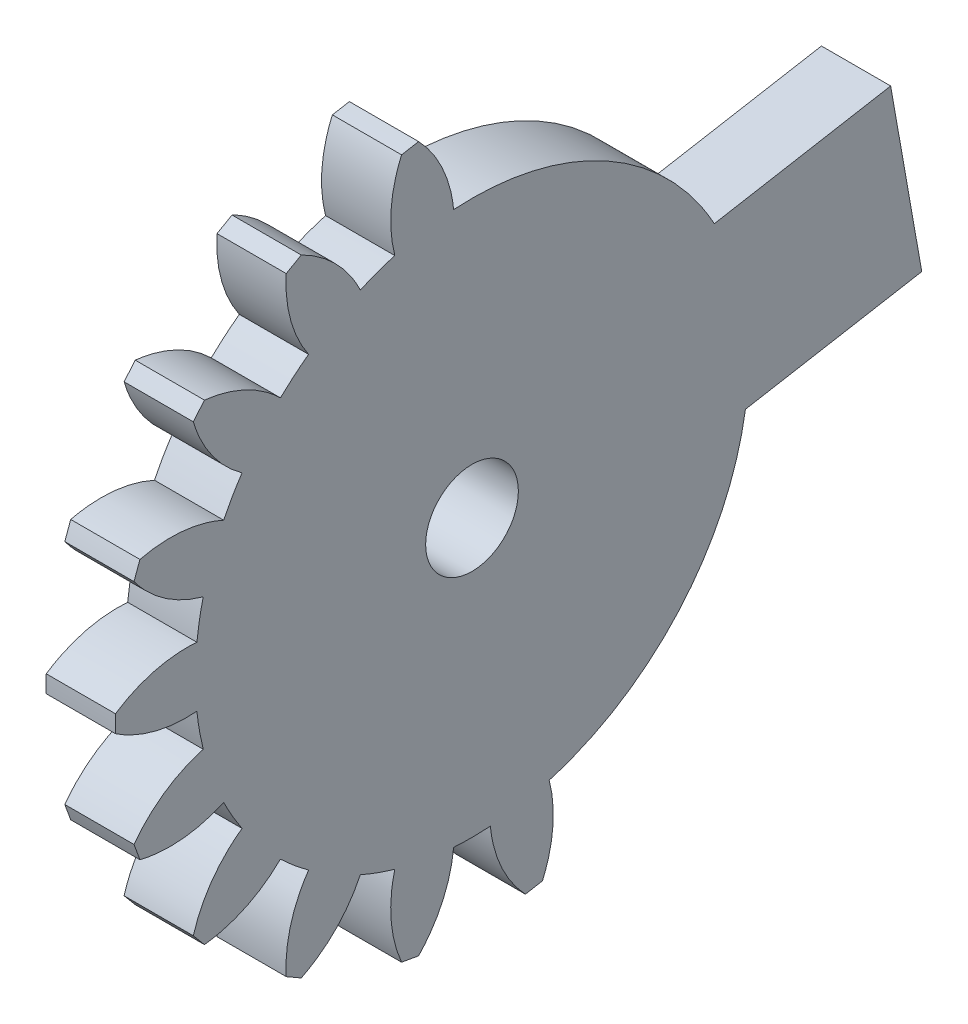
SolidWorks part; units mm, degrees
ref_plane "Plane1" through (0, 0, 0) normal (0, 0, 1) x (1, 0, 0)
ref_plane "Plane2" through (0, 0, 0) normal (0, 1, 0) x (1, 0, 0)
ref_plane "Plane3" through (0, 0, 0) normal (1, 0, 0) x (0, 0, -1)
sketch "HoldingSke" plane through (0, 0, 0) normal (0, 1, 0) x (1, 0, 0)
  line L0 (0, 0) -> (483.1367, -156.9806)
  line L1 (-15, 0) -> (100, 0) construction
  line L2 (0, 0) -> (-2.1039, 2.3779)
  line L3 (0, 0) -> (-11.863, 4.5341)
  line L4 (0, 0) -> (8.2133, 2.6687)
  line L5 (0, 0) -> (-47.5972, -17.7524)
  line L6 (0, 0) -> (-2.632, -1.7758)
  line L7 (-2.1039, 2.3779) -> (8.8308, 51.9871)
  line L8 (-76.2, 54.61) -> (-72.771, 54.61)
  line L9 (-71.009, 38.7566) -> (-53.1078, 45.2721)
  line L10 (-76.2, 71.12) -> (104.1128, 71.12)
  line L11 (0, 0) -> (-3.175, 0)
  line L12 (-76.2, 101.6) -> (-76.1492, 101.6)
  line L13 (24.9733, 27.94) -> (52.9518, 28.4284)
  line L14 (24.9733, 27.94) -> (25.0241, 27.9398)
  line L15 (24.9733, 27.94) -> (100.4021, 29.52)
  circle A0 centre (0, 0) radius 1.5875
  circle A1 centre (0, 0) radius 9.8552
  circle A2 centre (0, 0) radius 38.1
  circle A3 centre (0, 0) radius 1.5875
  dimension "MHD" = 19.7104
  dimension "Hub_dia" = 76.2
  dimension "Bore" = 3.175
  dimension "MBD" = 3.175
  dimension "Num_teeth" = 18
  dimension "Pitch_radius" = 180.3128
  dimension "Pitch" = 508
  dimension "Width" = 3.175
  dimension "Overall_len" = 50.8
  dimension "Show_teeth" = 18
  dimension "Thickness" = 3.175
  dimension "OAL" = 50.8001
  dimension "T_dim" = 3.429
  dimension "Ap" = 20
  dimension "H" = 19.05
  dimension "Backlash" = 0.0508
  dimension "Addendum_fac" = 1
  dimension "Dedendum_fac" = 1.2
  dimension "Clearance_fac" = 0.2
  dimension "Dedendum_add" = 0.0508
sketch "BasProSke" plane through (0, 0, 0) normal (0, 1, 0) x (1, 0, 0)
  line L0 (-10, 0) -> (60, 0) construction
  line L1 (0, 0) -> (0, 12.7)
  line L2 (0, 0) -> (3.175, 0)
  line L3 (3.175, 0) -> (3.175, 12.7)
  line L4 (3.175, 12.7) -> (0, 12.7)
  dimension "Diameter" = 25.4
  dimension "Thickness" = 3.175
revolve "Base-Revolve" add sketch "BasProSke" angle 360 about L0
sketch "TooCutSke" plane through (0, 0, 0) normal (1, 0, 0) x (0, 0, -1)
  line L1 (0, 0) -> (0, 107) construction
  line L2 (0, 0) -> (-1.085, 11.3784) construction
  line L3 (0, 0) -> (-3.9571, 22.4417) construction
  line L4 (-1.085, 11.3784) -> (-1.9785, 11.2208) construction
  arc A0 (0.6537, 9.8335) -> (-0.6537, 9.8335) centre (0, 0) ccw
  arc A1 (1.9234, 12.5792) -> (-1.9234, 12.5792) centre (0, 0) ccw
  circle A2 centre (0, 0) radius 11.43 construction
  circle A3 centre (0, 0) radius 10.7407 construction
  arc A4 (-0.6537, 9.8335) -> (-1.9234, 12.5792) centre (-5.2046, 9.3954) ccw
  arc A5 (1.9234, 12.5792) -> (0.6537, 9.8335) centre (5.2046, 9.3954) ccw
  dimension "Root_dia" = 19.7104
  dimension "Overcut_dia" = 25.4508
  dimension "Pitch_dia" = 22.86
  dimension "Base_dia" = 21.4814
  dimension "Flank_rad" = 4.572
  dimension "Half_ang" = 10
  dimension "Half_CT" = 0.9073
extrude "ToothCut" cut sketch "TooCutSke" along normal through all
fillet "Breaks" [suppressed] radius 0.0254
fillet "RootFillets" [suppressed] radius 0.3048
pattern_circular "TeethCuts" count 18 every 20 about axis through (-10, 0, 0) along (1, 0, 0) of "ToothCut", "RootFillets", "Breaks"
sketch "HubNeaOneSke" plane through (0, 0, 0) normal (-1, 0, 0) x (0, 0, 1)
  circle A0 centre (0, 0) radius 9.8552
  dimension "Diameter" = 19.7104
extrude "HubNearOne" [suppressed] add sketch "HubNeaOneSke" along normal blind 47.6251
sketch "HubNeaBotSke" plane through (0, 0, 0) normal (-1, 0, 0) x (0, 0, 1)
  circle A0 centre (0, 0) radius 9.8552
  dimension "Diameter" = 19.7104
extrude "HubNearBoth" [suppressed] add sketch "HubNeaBotSke" along normal blind 23.8125
ref_plane "FarPln" through (3.175, 0, 0) normal (1, 0, 0) x (0, 0, -1)
sketch "HubFarSke" plane through (3.175, 0, 0) normal (1, 0, 0) x (0, 0, -1)
  circle A0 centre (0, 0) radius 9.8552
  dimension "Diameter" = 19.7104
extrude "HubFar" [suppressed] add sketch "HubFarSke" along normal blind 23.8125
sketch "BorSke" plane through (0, 0, 0) normal (1, 0, 0) x (0, 0, -1)
  circle A0 centre (0, 0) radius 1.5875
  dimension "Diameter" = 3.175
extrude "Bore" cut sketch "BorSke" along normal mid plane 101.6001
sketch "KeySke" plane through (0, 0, 0) normal (1, 0, 0) x (0, 0, -1)
  line L0 (-0.127, 0) -> (-0.127, 1.8415)
  line L1 (-0.127, 1.8415) -> (0.127, 1.8415)
  line L2 (0.127, 1.8415) -> (0.127, 0)
  line L3 (0, 0) -> (0, 34) construction
  line L4 (-0.127, 0) -> (0.127, 0)
  dimension "Offset" = 1.8415
  dimension "Width" = 0.254
extrude "Keyway" [suppressed] cut sketch "KeySke" along normal mid plane 101.6001
pattern_circular "Keyway2" [suppressed] count 2 every 90 about axis through (-10, 0, 0) along (1, 0, 0)
sketch "Sketch3" plane through (0, 0, 0) normal (-1, 0, 0) x (0, 0, 1)
  line L0 (2.2053, 12.5071) -> (-2.2053, -12.5071) construction
  arc A0 (2.5076, 12.45) -> (1.9018, 12.5568) centre (0, 0) ccw construction
  arc A1 (-2.5076, -12.45) -> (-1.9018, -12.5568) centre (0, 0) ccw construction
sketch "Sketch7" plane through (0, 0, 0) normal (-1, 0, 0) x (0, 0, 1)
  line L0 (-8.6302, 4.7586) -> (-14.9088, 5.8657)
  line L1 (0, 9.8552) -> (0.5608, 13.3038)
  line L3 (-3.1735, -9.3303) -> (-4.1021, -12.668)
  line L4 (-14.9088, 5.8657) -> (-16.0158, -0.4129)
  line L5 (-16.0158, -0.4129) -> (-9.7373, -1.5199)
  line L6 (2.2053, 12.5071) -> (-2.2053, -12.5071) construction
  line L8 (0.5606, -0.0988) -> (50.9626, -8.9861) construction
  circle A1 centre (0, 0) radius 9.8552 construction
  arc A2 (-3.1735, -9.3303) -> (-9.7373, -1.5199) centre (0, 0) cw
  circle A3 centre (0, 0) radius 13.3156 construction
  arc A4 (0.5608, 13.3038) -> (-4.1021, -12.668) centre (0, 0) cw
  arc A5 (0, 9.8552) -> (-8.6302, 4.7586) centre (0, 0) ccw
  arc A6 (0.6537, 9.8335) -> (-0.6537, 9.8335) centre (0, 0) ccw construction
  circle A7 centre (0, 0) radius 1.5875 construction
  arc A8 (-2.749, 9.464) -> (-3.9775, 9.0169) centre (0, 0) ccw construction
  point P29 (-15.4623, 2.7264)
  dimension "D1" = 6.3754
  dimension "D7" = 26.6313
  dimension "D2" = 6.3754
  dimension "D3" = 84.453
extrude "Cut-Extrude-Thin1" cut sketch "Sketch7" against normal blind 5.08 and the other way blind 2.54 thin
sketch "Sketch8" plane through (0, 0, 0) normal (-1, 0, 0) x (0, 0, 1)
  line L0 (-14.9088, 5.8657) -> (-16.0158, -0.4129)
  line L1 (-14.9088, 5.8657) -> (-8.6302, 4.7586)
  line L2 (-16.0158, -0.4129) -> (-9.7373, -1.5199)
  line L3 (-8.6302, 4.7586) -> (-9.7373, -1.5199)
  arc A0 (0.6537, 9.8335) -> (-8.8429, 4.3507) centre (0, 0) ccw construction
extrude "Boss-Extrude1" add sketch "Sketch8" against normal up to surface (3.175 mm away) up to face at (3.175, -0.5968, 3.3848)
sketch "Sketch9" plane through (0, 0, 0) normal (-1, 0, 0) x (0, 0, 1)
  circle A1 centre (0, 0) radius 1.651
  dimension "D1" = 3.302
extrude "Cut-Extrude2" cut sketch "Sketch9" against normal up to surface (3.175 mm away) up to face at (3.175, -0.8052, 4.5666)
scale "Scale1" scale about centroid uniform scaling no x scale factor 1 y scale factor 1.288 z scale factor 1.288
equation "' \"Pitch@HoldingSke\" = 4"
equation "' \"Num_teeth@HoldingSke\" = 12"
equation "' \"Ap@HoldingSke\" =  20"
equation "' \"Width@HoldingSke\" = 0.5"
equation "' \"Hub_dia@HoldingSke\"= 1"
equation "' \"Overall_len@HoldingSke\" = 1.0"
equation "' \"Bore@HoldingSke\" = 0.75"
equation "' \"T_dim@HoldingSke\" = 0.85"
equation "' \"Width@KeySke\" = 0.25"
equation "' \"Show_teeth@HoldingSke\" = 13"
equation "' \"Backlash@HoldingSke\" = 0.009"
equation "' \"Addendum_fac@HoldingSke\" = 1.0"
equation "' \"Dedendum_fac@HoldingSke\" = 1.25"
equation "' \"Dedendum_add@HoldingSke\" = 0.00005"
equation "' \"Clearance_fac@HoldingSke\" = 0.25"
equation "' \"Pitch@HoldingSke\" = 0.5"
equation "' \"Num_teeth@HoldingSke\" = 23"
equation "' \"Show_teeth@HoldingSke\" = 23"
equation "' \"Backlash@HoldingSke\" = 0.0375"
equation "\"Overcut_dia@TooCutSke\" = (\"Num_teeth@HoldingSke\" + 2 * \"Addendum_fac@HoldingSke\") / \"Pitch@HoldingSke\" + 0.002"
equation "\"Pitch_dia@TooCutSke\" = \"Num_teeth@HoldingSke\" / \"Pitch@HoldingSke\""
equation "\"Base_dia@TooCutSke\" = \"Num_teeth@HoldingSke\" / \"Pitch@HoldingSke\" * cos((\"Ap@HoldingSke\"  * 3.14159265 / 180))"
equation "\"Root_dia@TooCutSke\" = (\"Num_teeth@HoldingSke\" + 2) / \"Pitch@HoldingSke\" - 2 * (\"Addendum_fac@HoldingSke\" + \"Dedendum_fac@HoldingSke\") / \"Pitch@HoldingSke\" - \"Dedendum_add@HoldingSke\" * 2"
equation "\"Half_ang@TooCutSke\" = 180 / \"Num_teeth@HoldingSke\""
equation "\"Half_CT@TooCutSke\" = \"Num_teeth@HoldingSke\" / \"Pitch@HoldingSke\" * sin((3.14159265 / 2 / \"Num_teeth@HoldingSke\")) / 2 - 7 * \"Backlash@HoldingSke\" / 4"
equation "\"Flank_rad@TooCutSke\" = \"Num_teeth@HoldingSke\" / \"Pitch@HoldingSke\" / 5"
equation "\"Radius@RootFillets\" = \"Clearance_fac@HoldingSke\" / \"Pitch@HoldingSke\" + \"Dedendum_add@HoldingSke\""
equation "\"Break_rad@Breaks\" = 0.02 / \"Pitch@HoldingSke\""
equation "\"Thickness@HoldingSke\" = \"Width@HoldingSke\""
equation "\"OAL@HoldingSke\" = \"Thickness@HoldingSke\""
equation "\"MHD@HoldingSke\" = (\"Num_teeth@HoldingSke\" + 2) / \"Pitch@HoldingSke\" - 2 * (\"Addendum_fac@HoldingSke\" + \"Dedendum_fac@HoldingSke\")  / \"Pitch@HoldingSke\" - \"Dedendum_add@HoldingSke\" * 2"
equation "\"MBD@HoldingSke\" = (\"Num_teeth@HoldingSke\" + 2) / \"Pitch@HoldingSke\" - 2 * (\"Addendum_fac@HoldingSke\" + \"Dedendum_fac@HoldingSke\")  / \"Pitch@HoldingSke\" - \"Dedendum_add@HoldingSke\" * 2 - 0.002"
equation "\"MHD@HoldingSke\" = ((sgn( \"MHD@HoldingSke\" - \"Hub_dia@HoldingSke\" )-1)*( \"MHD@HoldingSke\" - \"Hub_dia@HoldingSke\" ))/-2+ \"Hub_dia@HoldingSke\""
equation "\"MBD@HoldingSke\" = ((sgn( \"MBD@HoldingSke\" - \"Bore@HoldingSke\" )-1)*( \"MBD@HoldingSke\" - \"Bore@HoldingSke\" ))/-2+ \"Bore@HoldingSke\""
equation "\"OAL@HoldingSke\" = ((sgn( \"OAL@HoldingSke\" - \"Overall_len@HoldingSke\" )+1)*( \"OAL@HoldingSke\" - \"Overall_len@HoldingSke\" ))/2 + \"Overall_len@HoldingSke\" + 0.000002"
equation "\"Num_teeth@TeethCuts\" = int( \"Show_teeth@HoldingSke\" ) + 1"
equation "\"Num_teeth@TeethCuts\" = ((sgn( \"Num_teeth@TeethCuts\" - \"Num_teeth@HoldingSke\" )-1)*( \"Num_teeth@TeethCuts\" - \"Num_teeth@HoldingSke\" ))/-2+ \"Num_teeth@HoldingSke\""
equation "\"Num_teeth@TeethCuts\" = ((sgn( \"Num_teeth@TeethCuts\" - 2.0)+1)*( \"Num_teeth@TeethCuts\" - 2.0))/2 +2.0"
equation "\"Angle@TeethCuts\" = 360.0 / \"Num_teeth@HoldingSke\""
equation "\"Diameter@BasProSke\" = (\"Num_teeth@HoldingSke\" + 2 * \"Addendum_fac@HoldingSke\") / \"Pitch@HoldingSke\""
equation "\"Thickness@BasProSke\"  = \"Thickness@HoldingSke\""
equation "' \"Fillet_rad@BasProSke\" =  \"Thickness@HoldingSke\" * 0.05"
equation "\"MHD@HoldingSke\" = ((sgn( \"MHD@HoldingSke\" - \"Root_dia@TooCutSke\" )-1)*( \"MHD@HoldingSke\" - \"Root_dia@TooCutSke\" ))/-2+ \"Root_dia@TooCutSke\""
equation "\"Diameter@HubNeaOneSke\" = \"MHD@HoldingSke\""
equation "\"Length@HubNearOne\" = \"OAL@HoldingSke\" - \"Thickness@BasProSke\""
equation "\"Diameter@HubNeaBotSke\" = \"MHD@HoldingSke\""
equation "\"Length@HubNearBoth\" = ( \"OAL@HoldingSke\" - \"Thickness@BasProSke\" ) / 2.0"
equation "\"Thickness@FarPln\" = \"Thickness@BasProSke\""
equation "\"Diameter@HubFarSke\" = \"MHD@HoldingSke\""
equation "\"Length@HubFar\" = ( \"OAL@HoldingSke\" - \"Thickness@BasProSke\" ) / 2.0"
equation "\"Diameter@BorSke\" = \"MBD@HoldingSke\""
equation "\"D1@Bore\" = \"OAL@HoldingSke\" * 2.0"
equation "\"D1@Keyway\" = \"OAL@HoldingSke\" * 2.0"
equation "\"Offset@KeySke\" = \"T_dim@HoldingSke\" - \"MBD@HoldingSke\" / 2.0"
